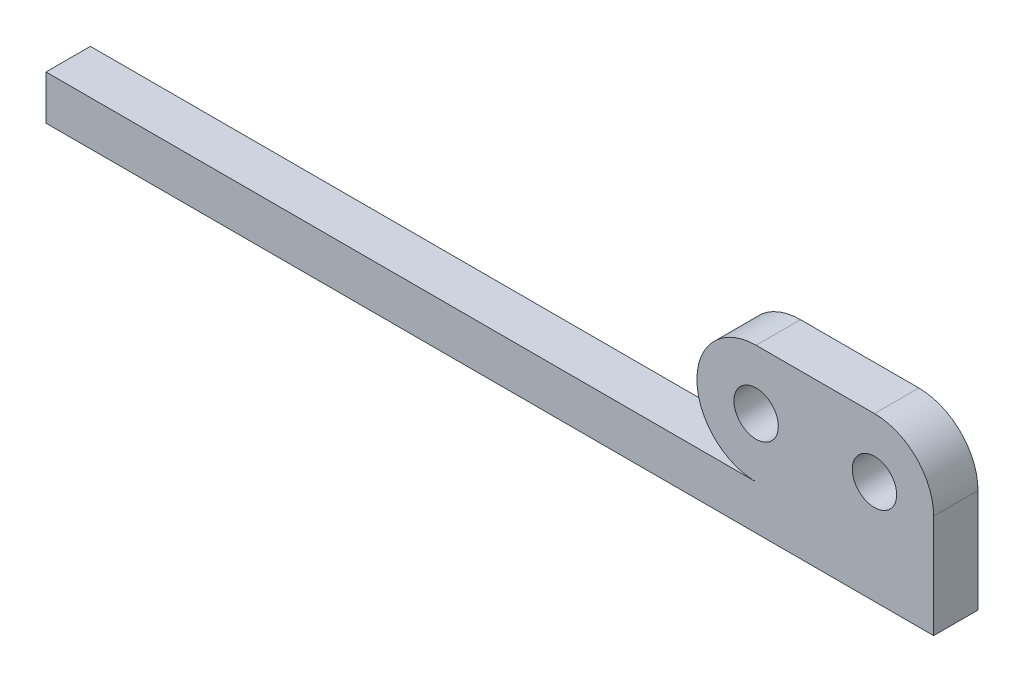
SolidWorks part; units mm, degrees
material "Acrílico (Impacto medio-alto)"
ref_plane "Alzado" through (0, 0, 0) normal (0, 0, 1) x (1, 0, 0)
ref_plane "Planta" through (0, 0, 0) normal (0, 1, 0) x (1, 0, 0)
ref_plane "Vista lateral" through (0, 0, 0) normal (1, 0, 0) x (0, 0, -1)
sketch "Croquis1" plane through (0, 0, 0) normal (0, 0, 1) x (1, 0, 0)
  line L0 (12, 0) -> (12, -4)
  line L1 (0, -4) -> (8, -4)
  line L2 (0, -4) -> (0, 4)
  line L3 (0, 4) -> (8, 4)
  line L4 (8, -4) -> (8, 4)
  line L13 (12, -4) -> (-48, -4)
  line L14 (12, -4) -> (12, -7)
  line L15 (12, -7) -> (-48, -7)
  line L16 (-48, -4) -> (-48, -7)
  circle A0 centre (0, 0) radius 1.5
  circle A1 centre (0, 0) radius 4
  circle A2 centre (8, 0) radius 1.5
  circle A3 centre (8, 0) radius 4
  point P11 (0, 0)
  point P12 (8, 0)
  dimension "D1" = 8
  dimension "D2" = 3
  dimension "D3" = 8
  dimension "D4" = 3
  dimension "D5" = 8
  dimension "D6" = 8
  dimension "D7" = 60
  dimension "D8" = 3
  dimension "D9" = 4
extrude "Saliente-Extruir1" add sketch "Croquis1" along normal blind 3 contours A3 L3 A1 | A3 A1 L1 | A3 L13 L0 | A0 | A2
